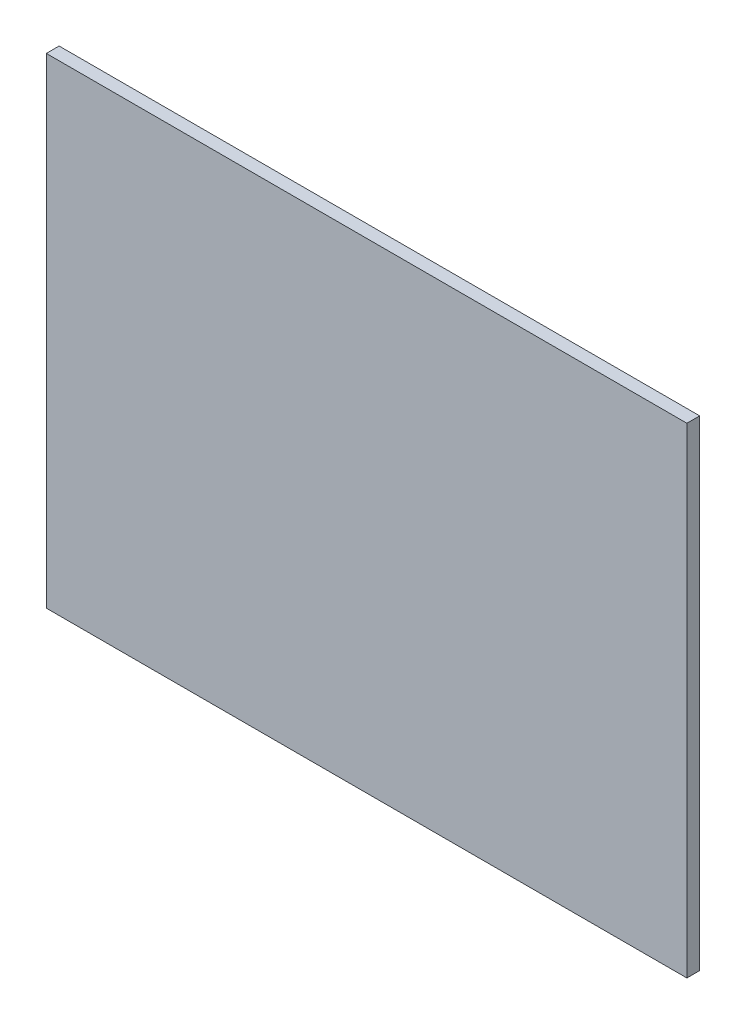
SolidWorks part; units mm, degrees
ref_plane "Front Plane" through (0, 0, 0) normal (0, 0, 1) x (1, 0, 0)
ref_plane "Top Plane" through (0, 0, 0) normal (0, 1, 0) x (1, 0, 0)
ref_plane "Right Plane" through (0, 0, 0) normal (1, 0, 0) x (0, 0, -1)
sketch "Sketch1" plane through (0, 0, 0) normal (0, 0, 1) x (1, 0, 0)
  line L1 (-100, 75) -> (100, 75)
  line L2 (-100, 75) -> (-100, -75)
  line L3 (-100, -75) -> (100, -75)
  line L4 (100, 75) -> (100, -75)
  line L5 (-100, 75) -> (100, -75) construction
  line L6 (-100, -75) -> (100, 75) construction
  point P0 (0, 0)
  dimension "D1" = 200
  dimension "D2" = 150
extrude "Boss-Extrude1" add sketch "Sketch1" along normal blind 4
